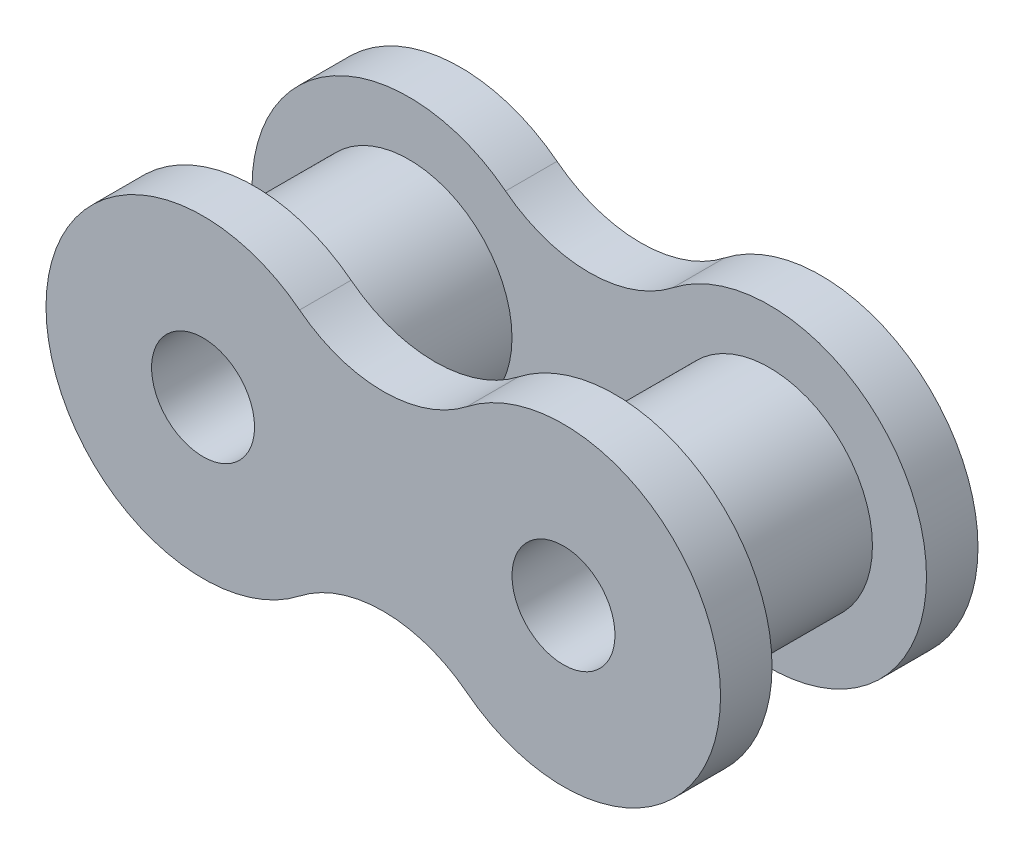
SolidWorks part; units mm, degrees
material "AISI 304"
ref_plane "Alzado" through (0, 0, 0) normal (0, 0, 1) x (1, 0, 0)
ref_plane "Planta" through (0, 0, 0) normal (0, 1, 0) x (1, 0, 0)
ref_plane "Vista lateral" through (0, 0, 0) normal (1, 0, 0) x (0, 0, -1)
sketch "Croquis1" plane through (0, 0, 0) normal (0, 0, 1) x (1, 0, 0)
  line L0 (0, 12.0796) -> (0, 3.6946) construction
  line L1 (0, 3.6946) -> (0, -3.6946) construction
  line L2 (-14.3186, 0) -> (16.5828, 0) construction
  line L3 (0, -3.6946) -> (0, -11.0763) construction
  arc A6 (-3.2504, 4.8115) -> (-3.2504, -4.8115) centre (-7, 0) ccw
  circle A7 centre (-7, 0) radius 2
  circle A8 centre (7, 0) radius 2
  arc A9 (3.2504, 4.8115) -> (3.2504, -4.8115) centre (7, 0) cw
  arc A10 (-3.2504, 4.8115) -> (3.2504, 4.8115) centre (0, 8.9826) ccw
  arc A11 (-3.2504, -4.8115) -> (3.2504, -4.8115) centre (0, -8.9826) cw
  dimension "D1" = 4
  dimension "D2" = 6.1
  dimension "D3" = 5.288
  dimension "D4" = 14.3186
  dimension "D5" = 3.2504
  dimension "D6" = 11.0763
extrude "Saliente-Extruir1" add sketch "Croquis1" along normal blind 2
sketch "Croquis3" plane through (0, 0, 2) normal (0, 0, 1) x (1, 0, 0)
  circle A0 centre (7, 0) radius 2 construction
  circle A1 centre (-7, 0) radius 2 construction
  circle A2 centre (7, 0) radius 2
  circle A3 centre (-7, 0) radius 2
  arc A4 (-3.2504, 4.8115) -> (3.2504, 4.8115) centre (0, 8.9826) ccw
  arc A5 (-3.2504, 4.8115) -> (-3.2504, -4.8115) centre (-7, 0) ccw
  arc A6 (3.2504, -4.8115) -> (-3.2504, -4.8115) centre (0, -8.9826) ccw
  arc A7 (3.2504, -4.8115) -> (3.2504, 4.8115) centre (7, 0) ccw
  arc A8 (-3.2504, 4.8115) -> (3.2504, 4.8115) centre (0, 8.9826) ccw
  arc A9 (-3.2504, 4.8115) -> (-3.2504, -4.8115) centre (-7, 0) ccw
  arc A10 (3.2504, -4.8115) -> (-3.2504, -4.8115) centre (0, -8.9826) ccw
  arc A11 (3.2504, -4.8115) -> (3.2504, 4.8115) centre (7, 0) ccw
  circle A12 centre (-7, 0) radius 4
  circle A13 centre (7, 0) radius 4
  circle M8 centre (-7, 0) radius 2
  circle M13 centre (7, 0) radius 2
  dimension "D2" = 8
  dimension "D1" = 0
extrude "Saliente-Extruir2" add sketch "Croquis3" along normal blind 8 contours A12 M8 | A13 M13
ref_plane "Plano1" through (0, 0, 5) normal (0, 0, 1) x (1, 0, 0)
mirror "Simetría1" about plane through (0, 0, 5) normal (0, 0, 1) of "Saliente-Extruir1"
